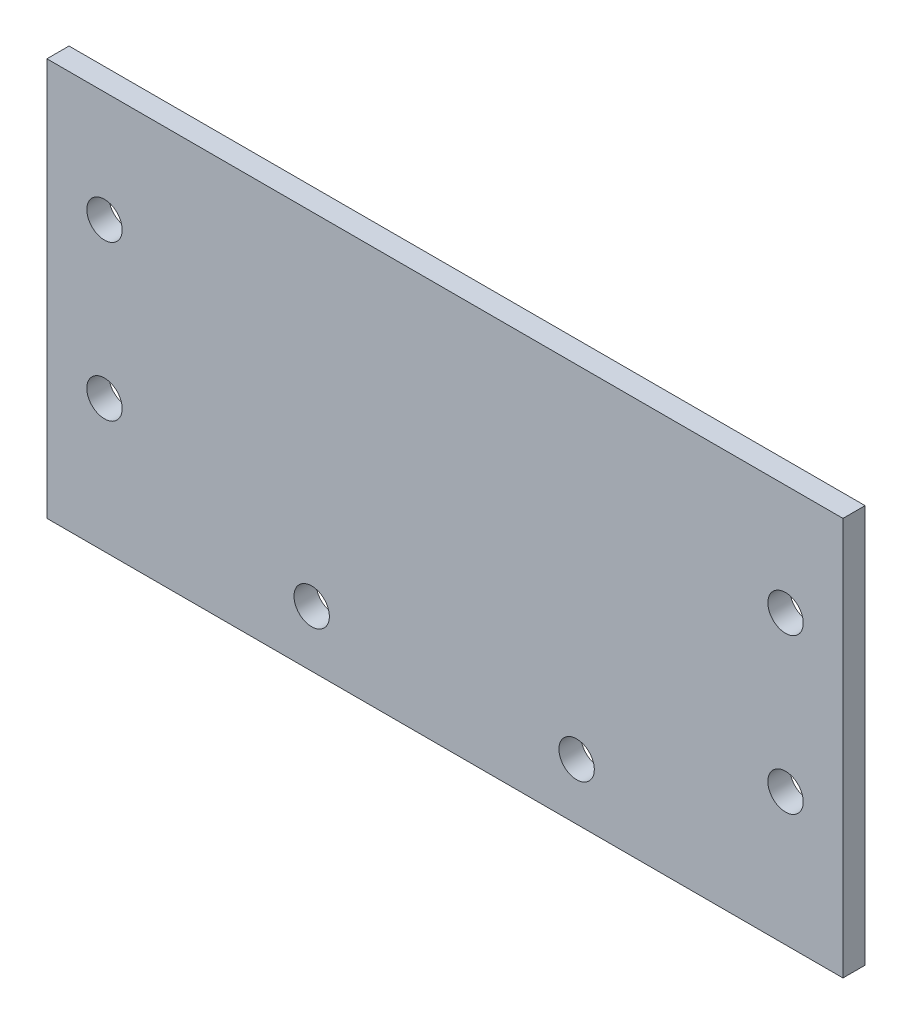
SolidWorks part; units mm, degrees
ref_plane "Front Plane" through (0, 0, 0) normal (0, 0, 1) x (1, 0, 0)
ref_plane "Top Plane" through (0, 0, 0) normal (0, 1, 0) x (1, 0, 0)
ref_plane "Right Plane" through (0, 0, 0) normal (1, 0, 0) x (0, 0, -1)
sketch "Sketch1" plane through (0, 0, 0) normal (0, 0, 1) x (1, 0, 0)
  line L0 (-30.2417, 30) -> (199.5204, 30) construction
  line L1 (0, 0) -> (180, 0)
  line L2 (0, 0) -> (0, 90)
  line L3 (0, 90) -> (180, 90)
  line L4 (180, 0) -> (180, 90)
  line L5 (-37.5745, 65) -> (203.0757, 65) construction
  line L6 (13, 105.7858) -> (13, -17.7613) construction
  line L7 (167, 105.7858) -> (167, -23.9831) construction
  line L8 (-22.2422, 13) -> (188.6323, 13) construction
  line L9 (60, 28.6799) -> (60, -12.8728) construction
  line L10 (120, 28.6799) -> (120, -12.8728) construction
  dimension "D1" = 180
  dimension "D2" = 90
  dimension "D3" = 13
  dimension "D4" = 13
  dimension "D5" = 47
  dimension "D6" = 107
  dimension "D7" = 154
  dimension "D8" = 30
  dimension "D9" = 35
extrude "Boss-Extrude1" add sketch "Sketch1" along normal blind 5 contours L3 L4 L1 L2
hole_wizard "Ø1.0mm Dowel Hole1" positions "Sketch6" profile "Sketch7" hole size "Ø1.0" standard "ISO" end condition through all
sketch "Sketch6" plane through (0, 0, 5) normal (0, 0, 1) x (1, 0, 0)
  point P2 (119.7741, 12.7162)
  point P4 (59.8661, 12.7162)
  point P6 (13.0182, 29.998)
  point P8 (13.0182, 64.9974)
  point P10 (167.0148, 64.9974)
  point P12 (167.0148, 29.998)
sketch "Sketch7" plane through (119.7741, 12.7162, 5) normal (1, 0, 0) x (0, -1, 0)
  line L0 (0, 0) -> (0, 5)
  line L1 (0, 5) -> (4, 5)
  line L2 (4, 5) -> (4, 0)
  line L5 (4, 0) -> (0, 0)
  line L11 (0, -6.35) -> (0, 107.95) construction
  dimension "Thru Hole Dia." = 8
  dimension "Thru Hole Depth" = 5
